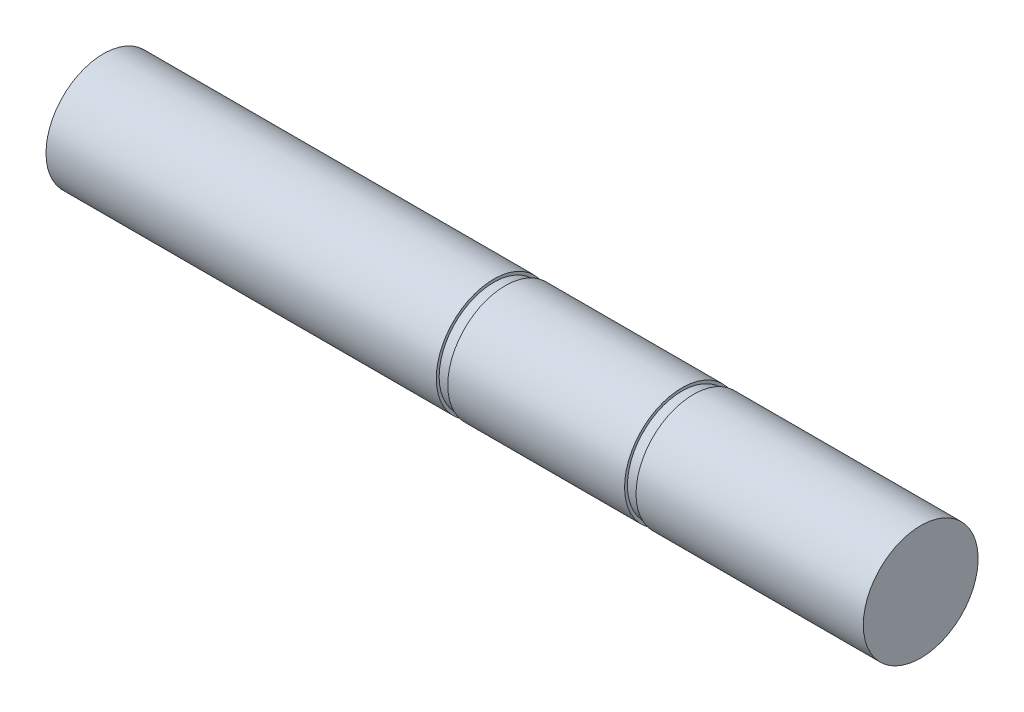
SolidWorks part; units mm, degrees
material "5052-H32"
ref_plane "Front Plane" through (0, 0, 0) normal (0, 0, 1) x (1, 0, 0)
ref_plane "Top Plane" through (0, 0, 0) normal (0, 1, 0) x (1, 0, 0)
ref_plane "Right Plane" through (0, 0, 0) normal (1, 0, 0) x (0, 0, -1)
sketch "Sketch2" plane through (0, 0, 0) normal (0, 0, 1) x (1, 0, 0)
  line L0 (-0.5, 2.5) -> (-0.5, 0)
  line L1 (-0.5, 4) -> (-0.5, -4) construction
  line L2 (-0.5, 0) -> (35.1, 0)
  line L3 (35.1, 4) -> (35.1, -4) construction
  line L4 (35.1, 0) -> (35.1, 2.5)
  line L5 (35.1, 2.5) -> (25.2, 2.5)
  line L6 (25.2, 2.5) -> (25.2, 2.375)
  line L7 (25.2, 2.375) -> (24.7, 2.375)
  line L8 (24.7, 2.375) -> (24.7, 2.5)
  line L9 (24.7, 2.5) -> (17, 2.5)
  line L10 (17, 2.5) -> (17, 2.375)
  line L11 (17, 2.375) -> (16.5, 2.375)
  line L12 (16.5, 2.375) -> (16.5, 2.5)
  line L13 (16.5, 2.5) -> (-0.5, 2.5)
  line L14 (16.6, 2.5) -> (16.6, 2.375) construction
  line L15 (16.6, 2.375) -> (16.6, 2.5) construction
revolve "Revolve1" add sketch "Sketch2" angle 360 about L2
